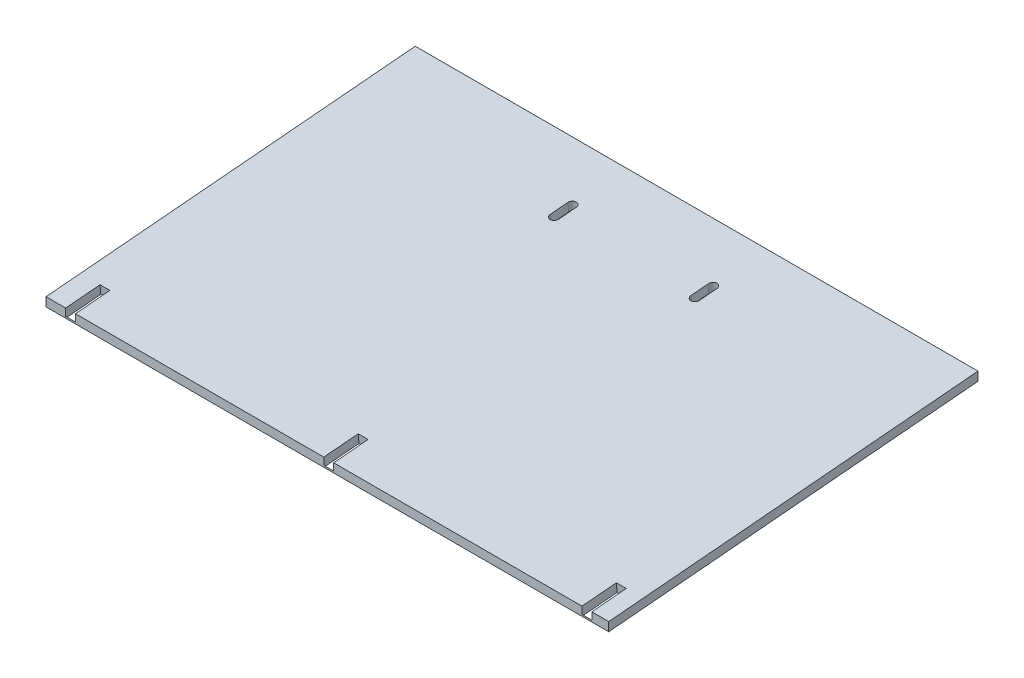
SolidWorks part; units mm, degrees
material "Acrylic (Medium-high impact)"
ref_plane "Front" through (0, 0, 0) normal (0, 0, 1) x (1, 0, 0)
ref_plane "Top" through (0, 0, 0) normal (0, 1, 0) x (1, 0, 0)
ref_plane "Right" through (0, 0, 0) normal (1, 0, 0) x (0, 0, -1)
sketch "Sketch1" plane through (0, 0, 0) normal (1, 0, 0) x (0, 0, -1)
  line L0 (107.95, -4.3375) -> (107.95, -7.5246)
  line L1 (107.95, -7.5246) -> (241.3, 4.142)
  line L2 (241.3, 4.142) -> (241.3, 7.3291)
  line L3 (241.3, 7.3291) -> (107.95, -4.3375)
  line L4 (241.3, -25.458) -> (241.3, -28.506) construction
  point P3 (241.3, 5.7356)
  dimension "D1" = 133.35
  dimension "D2" = 95
  dimension "D3" = 3.175
extrude "Boss-Extrude1" add sketch "Sketch1" along normal blind 203.2 contours L3 L0 L1 L2
sketch "Sketch2" plane through (0, -13.6772, -1.1966) normal (0, 0.9962, 0.0872) x (1, 0, 0)
  line L0 (101.6, 241.6311) -> (101.6, 43.4647) construction
  line L2 (203.2, 241.0206) -> (0, 241.0206) construction
  line L3 (0, 241.0206) -> (0, 107.1612) construction
  line L4 (74.676, 221.3356) -> (74.676, 214.9856)
  line L5 (77.724, 221.3356) -> (77.724, 214.9856)
  line L6 (128.524, 221.3356) -> (128.524, 214.9856)
  line L7 (125.476, 221.3356) -> (125.476, 214.9856)
  arc A1 (74.676, 221.3356) -> (77.724, 221.3356) centre (76.2, 221.3356) cw
  arc A2 (77.724, 214.9856) -> (74.676, 214.9856) centre (76.2, 214.9856) cw
  arc A3 (128.524, 221.3356) -> (125.476, 221.3356) centre (127, 221.3356) ccw
  arc A4 (125.476, 214.9856) -> (128.524, 214.9856) centre (127, 214.9856) ccw
  point P0 (74.676, 218.1606)
  point P5 (101.6, 241.0206)
  dimension "D1" = 22.86
  dimension "D2" = 6.35
  dimension "D3" = 3.048
  dimension "D4" = 76.2
extrude "Cut-Extrude1" cut sketch "Sketch2" against normal through all
sketch "Sketch3" plane through (0, -13.6772, -1.1966) normal (0, 0.9962, 0.0872) x (1, 0, 0)
  line L1 (7.0926, 106.9367) -> (10.6486, 106.9367)
  line L2 (7.0926, 106.9367) -> (7.0926, 119.6367)
  line L3 (7.0926, 119.6367) -> (10.6486, 119.6367)
  line L4 (10.6486, 106.9367) -> (10.6486, 119.6367)
  line L6 (100.3106, 106.9367) -> (100.3106, 119.6367)
  line L7 (100.3106, 106.9367) -> (103.8666, 106.9367)
  line L8 (103.8666, 106.9367) -> (103.8666, 119.6367)
  line L9 (100.3106, 119.6367) -> (103.8666, 119.6367)
  line L10 (193.5286, 106.9367) -> (193.5286, 119.6367)
  line L11 (193.5286, 106.9367) -> (197.0846, 106.9367)
  line L12 (197.0846, 106.9367) -> (197.0846, 119.6367)
  line L13 (193.5286, 119.6367) -> (197.0846, 119.6367)
  line L14 (7.0926, 106.9367) -> (100.3106, 106.9367) construction
  dimension "D1" = 3.556
  dimension "D3" = 93.218
  dimension "D4" = 12.7
  dimension "D2" = 3
extrude "Cut-Extrude2" cut sketch "Sketch3" against normal up to next
ref_plane "Plane1" through (197.0846, -3.2502, -120.378) normal (0, 0.0872, -0.9962) x (-1, 0, 0)
